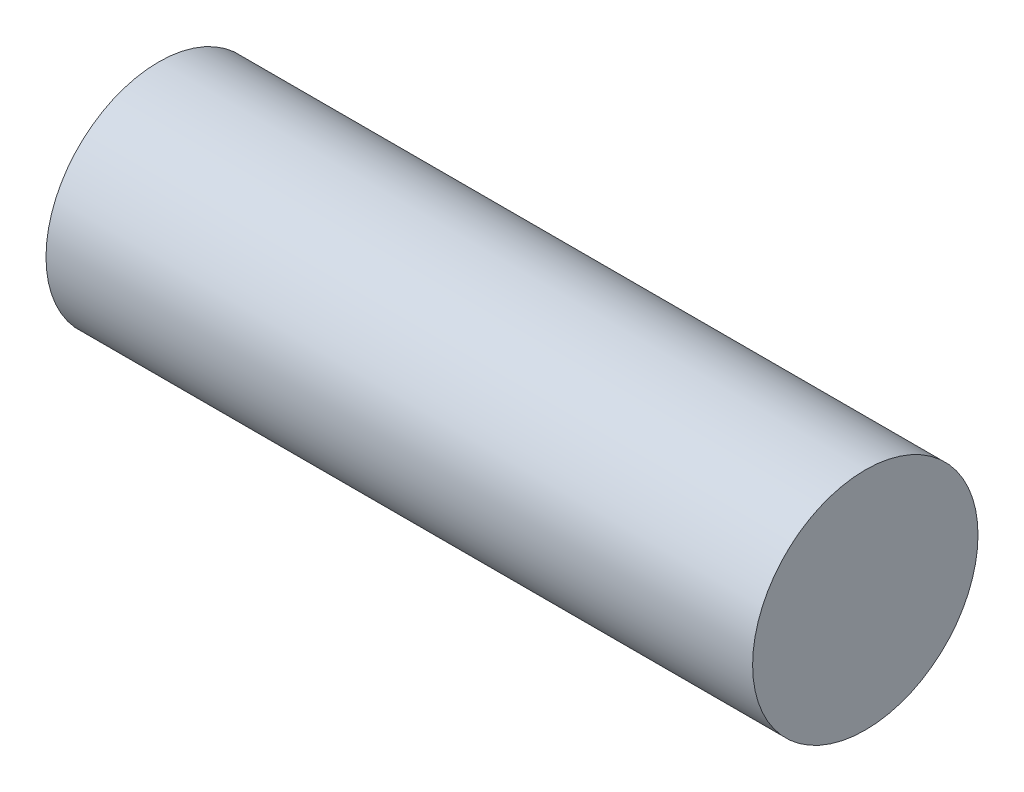
SolidWorks part; units mm, degrees
ref_plane "前视基准面" through (0, 0, 0) normal (0, 0, 1) x (1, 0, 0)
ref_plane "上视基准面" through (0, 0, 0) normal (0, 1, 0) x (1, 0, 0)
ref_plane "右视基准面" through (0, 0, 0) normal (1, 0, 0) x (0, 0, -1)
sketch "Sketch1" plane through (0, 0, 0) normal (1, 0, 0) x (0, 0, -1)
  circle A0 centre (0, 0) radius 9.25
  dimension "D1" = 18.5
extrude "Boss-Extrude1" add sketch "Sketch1" along normal blind 58
sketch "Sketch2" plane through (0, 0, 0) normal (-1, 0, 0) x (0, 0, 1)
  line L0 (0, -4) -> (0, 4) construction
  line L1 (0, 0) -> (3.3979, 0) construction
  circle A0 centre (0, 4) radius 2.5
  circle A1 centre (0, -4) radius 2.5
  point P4 (0, 0)
  dimension "D1" = 8
  dimension "D2" = 5
extrude "Boss-Extrude2" add sketch "Sketch2" along normal blind 1
